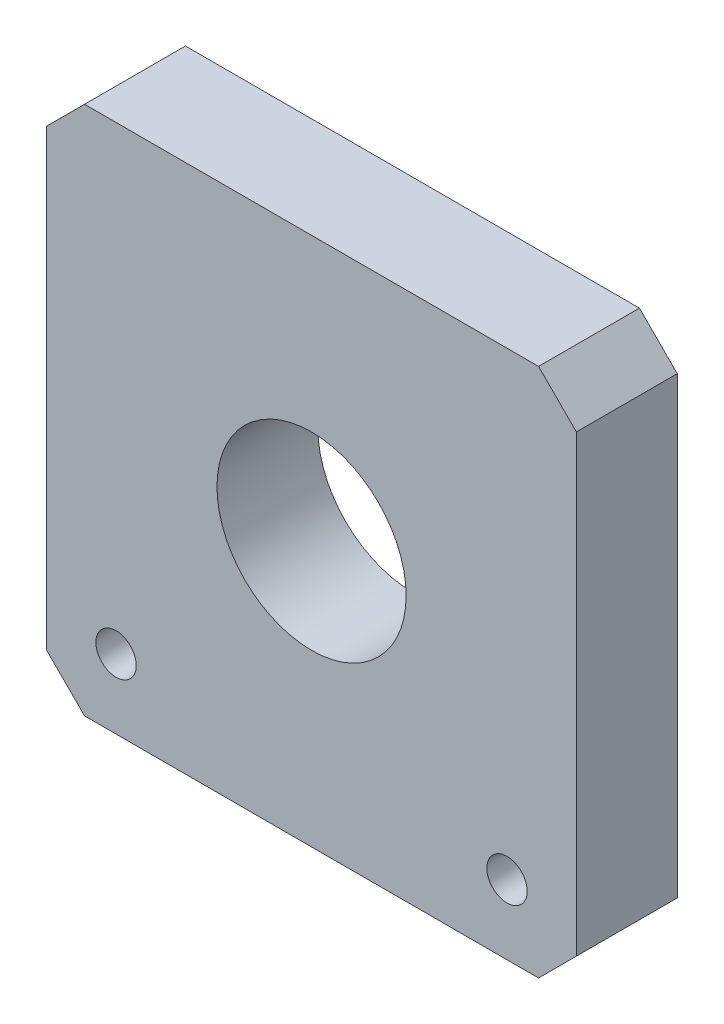
SolidWorks part; units mm, degrees
ref_plane "Front Plane" through (0, 0, 0) normal (0, 0, 1) x (1, 0, 0)
ref_plane "Top Plane" through (0, 0, 0) normal (0, 1, 0) x (1, 0, 0)
ref_plane "Right Plane" through (0, 0, 0) normal (1, 0, 0) x (0, 0, -1)
sketch "Sketch1" plane through (0, 0, 0) normal (0, 0, 1) x (1, 0, 0)
  line L1 (0, 0) -> (42, 0)
  line L2 (0, 0) -> (0, 42)
  line L3 (0, 42) -> (42, 42)
  line L4 (42, 0) -> (42, 42)
  dimension "D1" = 42
  dimension "D2" = 42
extrude "Boss-Extrude1" add sketch "Sketch1" along normal blind 8
sketch "Sketch2" plane through (0, 0, 8) normal (0, 0, 1) x (1, 0, 0)
  line L0 (42, 0) -> (42, 42) construction
  line L1 (0, 0) -> (42, 0) construction
  line L2 (36.5, 5.5) -> (5.5, 5.5) construction
  line L3 (21, 42) -> (21, 21) construction
  line L4 (42, 42) -> (0, 42) construction
  line L5 (0, 42) -> (0, 0) construction
  circle A0 centre (36.5, 5.5) radius 1.6
  circle A1 centre (5.5, 5.5) radius 1.6
  circle A2 centre (21, 21) radius 7.5
  dimension "D1" = 5.5
  dimension "D2" = 5.5
  dimension "D3" = 3.2
  dimension "D5" = 3.2
  dimension "D8" = 15
  dimension "D4" = 31
  dimension "D6" = 21
  dimension "D7" = 21
extrude "Cut-Extrude1" cut sketch "Sketch2" against normal blind 9
chamfer "Chamfer1" distance 3 angle 45 4 edges at (42, 0, 4) (0, 0, 4) (42, 42, 4) (0, 42, 4)
